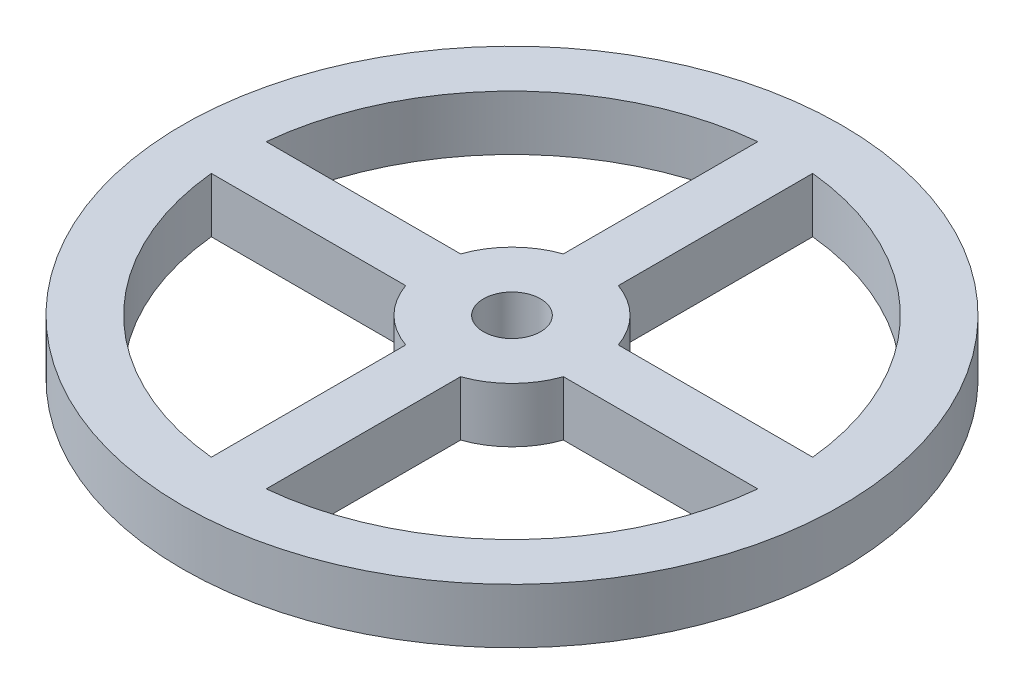
SolidWorks part; units mm, degrees
material "ABS"
ref_plane "Front Plane" through (0, 0, 0) normal (0, 0, 1) x (1, 0, 0)
ref_plane "Top Plane" through (0, 0, 0) normal (0, 1, 0) x (1, 0, 0)
ref_plane "Right Plane" through (0, 0, 0) normal (1, 0, 0) x (0, 0, -1)
sketch "Sketch1" plane through (0, 0, 0) normal (0, 1, 0) x (1, 0, 0)
  circle A0 centre (0, 0) radius 3.302
  circle A1 centre (0, 0) radius 38.1
  point P9 (0, 0)
  dimension "D1" = 6.604
  dimension "D2" = 76.2
extrude "Boss-Extrude1" add sketch "Sketch1" along normal blind 6.35
sketch "Sketch2" plane through (0, 0, 0) normal (0, 1, 0) x (1, 0, 0)
  line L0 (-31.5909, 3.175) -> (-9.1148, 3.175)
  line L1 (-3.175, 31.5909) -> (-3.175, 9.1148)
  line L2 (0, 36.4399) -> (0, 7.0337) construction
  line L3 (0, 0) -> (-49.1139, 0) construction
  circle A0 centre (0, 0) radius 3.302 construction
  circle A1 centre (0, 0) radius 38.1 construction
  arc A2 (-3.175, 31.5909) -> (-31.5909, 3.175) centre (0, 0) ccw
  arc A3 (-3.175, 9.1148) -> (-9.1148, 3.175) centre (0, 0) ccw
  point P2 (-31.6361, 2.6875)
  dimension "D1" = 6.604
  dimension "D2" = 76.2
  dimension "D4" = 6.35
  dimension "D5" = 6.35
  dimension "D3" = 3.175
  dimension "D6" = 3.175
extrude "Cut-Extrude4" cut sketch "Sketch2" along normal through all contours L1 A3 L0 A2
pattern_circular "CirPattern1" count 4 over 360 about axis through (0, 0, 0) along (0, 1, 0) of "Cut-Extrude4"
